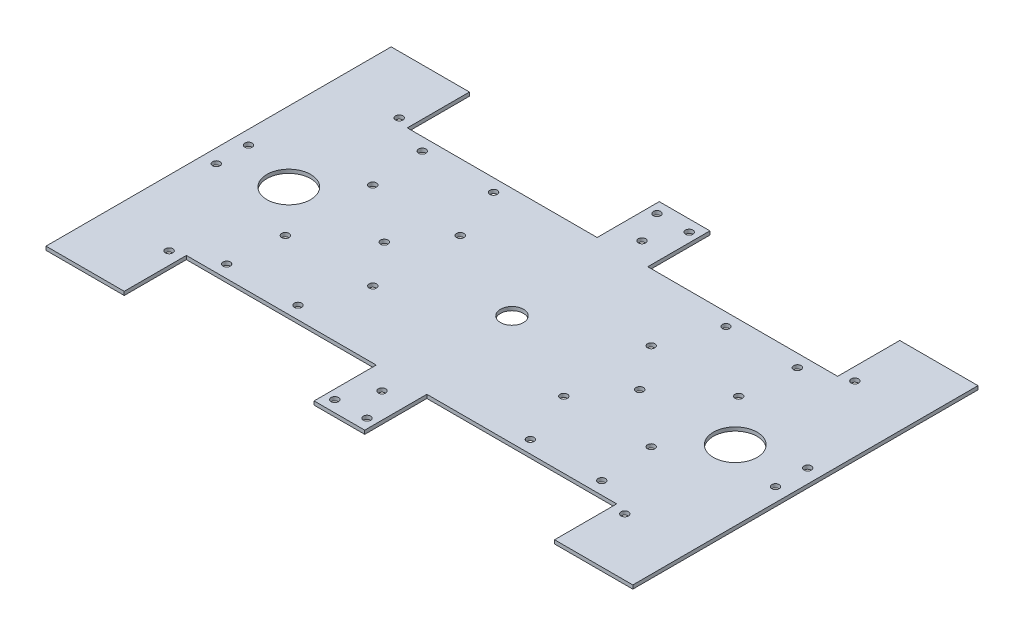
SolidWorks part; units mm, degrees
ref_plane "前视基准面" through (0, 0, 0) normal (0, 0, 1) x (1, 0, 0)
ref_plane "上视基准面" through (0, 0, 0) normal (0, 1, 0) x (1, 0, 0)
ref_plane "右视基准面" through (0, 0, 0) normal (1, 0, 0) x (0, 0, -1)
other "Configuration Table"
sketch "草图2" plane through (0, 0, 0) normal (0, 1, 0) x (1, 0, 0)
  line L0 (-11, 75) -> (11, 75)
  line L1 (-127.5, 75) -> (-93.5, 75)
  line L2 (-127.5, 75) -> (-127.5, -75)
  line L3 (-127.5, -75) -> (-93.5, -75)
  line L4 (127.5, 75) -> (127.5, -75)
  line L16 (-11, 75) -> (-11, 48)
  line L17 (-127.5, 75) -> (-93.5, 75)
  line L19 (0, 75) -> (0, -75) construction
  line L20 (-93.5, 75) -> (-93.5, 48)
  line L21 (-93.5, 48) -> (-11, 48)
  line L22 (93.5, 48) -> (11, 48)
  line L23 (11, 75) -> (11, 48)
  line L24 (93.5, 75) -> (93.5, 48)
  line L25 (-127.5, 0) -> (127.5, 0) construction
  line L26 (93.5, -75) -> (93.5, -48)
  line L27 (93.5, -48) -> (11, -48)
  line L28 (11, -75) -> (11, -48)
  line L29 (-11, -75) -> (-11, -48)
  line L30 (-93.5, -48) -> (-11, -48)
  line L31 (-93.5, -75) -> (-93.5, -48)
  line L32 (-11, 75) -> (11, 75)
  line L33 (93.5, 75) -> (127.5, 75)
  line L34 (-11, -75) -> (11, -75)
  line L35 (93.5, -75) -> (127.5, -75)
  circle A5 centre (0, 0) radius 5
  point P0 (0, 0)
  point P5 (0.2034, 0.1197)
  point P8 (-127.5, 0)
  point P9 (0.2034, 0.1197)
  point P12 (0.2034, 0.1197)
  point P14 (0, 75)
  point P17 (0.2034, 0.1197)
  point P26 (0, 0)
  dimension "D3" = 27
  dimension "D6" = 10
  dimension "D1" = 255
  dimension "D2" = 150
  dimension "D4" = 34
  dimension "D5" = 22
extrude "凸台-拉伸1" add sketch "草图2" along normal mid plane 1.6
sketch "草图3" plane through (0, 0.8, 0) normal (0, 1, 0) x (1, 0, 0)
  line L0 (-11, -48) -> (-16.5, -48)
  line L1 (0, 75) -> (0, -75) construction
  line L2 (-16.5, -48) -> (-71.5, -48)
  line L3 (-16.5, -48) -> (-16.5, -46)
  line L4 (-16.5, -46) -> (-71.5, -46)
  line L5 (-71.5, -48) -> (-71.5, -46)
  line L6 (-127.5, 0) -> (127.5, 0) construction
  line L7 (16.5, -46) -> (71.5, -46)
  line L8 (71.5, -48) -> (71.5, -46)
  line L9 (16.5, -48) -> (71.5, -48)
  line L10 (16.5, -48) -> (16.5, -46)
  line L11 (16.5, 48) -> (16.5, 46)
  line L12 (16.5, 48) -> (71.5, 48)
  line L13 (71.5, 48) -> (71.5, 46)
  line L14 (16.5, 46) -> (71.5, 46)
  line L15 (-16.5, 46) -> (-71.5, 46)
  line L16 (-71.5, 48) -> (-71.5, 46)
  line L17 (-16.5, 48) -> (-71.5, 48)
  line L18 (-16.5, 48) -> (-16.5, 46)
  line L20 (93.5, -48) -> (93.5, -75)
  line L21 (93.5, -75) -> (127.5, -75)
  line L22 (127.5, -75) -> (127.5, 75)
  line L23 (127.5, 75) -> (93.5, 75)
  line L24 (93.5, 75) -> (93.5, 48)
  line L25 (93.5, 48) -> (11, 48)
  line L26 (11, 48) -> (11, 75)
  line L27 (11, 75) -> (-11, 75)
  line L28 (-11, 75) -> (-11, 48)
  line L29 (-11, 48) -> (-93.5, 48)
  line L30 (-93.5, 48) -> (-93.5, 75)
  line L31 (-93.5, 75) -> (-127.5, 75)
  line L32 (-127.5, 75) -> (-127.5, -75)
  line L33 (-127.5, -75) -> (-93.5, -75)
  line L34 (-93.5, -75) -> (-93.5, -48)
  line L35 (-93.5, -48) -> (-11, -48)
  line L36 (-11, -48) -> (-11, -75)
  line L37 (-11, -75) -> (11, -75)
  line L38 (11, -75) -> (11, -48)
  line L39 (11, -48) -> (93.5, -48)
  line L40 (93.5, -48) -> (93.5, -75)
  line L41 (93.5, -75) -> (127.5, -75)
  line L42 (127.5, -75) -> (127.5, 75)
  line L43 (127.5, 75) -> (93.5, 75)
  line L44 (93.5, 75) -> (93.5, 48)
  line L45 (93.5, 48) -> (11, 48)
  line L46 (11, 48) -> (11, 75)
  line L47 (11, 75) -> (-11, 75)
  line L48 (-11, 75) -> (-11, 48)
  line L49 (-11, 48) -> (-93.5, 48)
  line L50 (-93.5, 48) -> (-93.5, 75)
  line L51 (-93.5, 75) -> (-127.5, 75)
  line L52 (-127.5, 75) -> (-127.5, -75)
  line L53 (-127.5, -75) -> (-93.5, -75)
  line L54 (-93.5, -75) -> (-93.5, -48)
  line L55 (-93.5, -48) -> (-11, -48)
  line L56 (-11, -48) -> (-11, -75)
  line L57 (-11, -75) -> (11, -75)
  line L58 (11, -75) -> (11, -48)
  line L59 (11, -48) -> (93.5, -48)
  point P20 (0, 0)
  dimension "D2" = 5.5
  dimension "D3" = 2
  dimension "D4" = 55
  dimension "D1" = 0
sketch "草图5" plane through (0, -0.8, 0) normal (0, -1, 0) x (1, 0, 0)
  line L0 (0, -56.5) -> (0, 56.5) construction
  line L1 (0, 0) -> (0, 70) construction
  line L2 (7, 70) -> (-7, 70) construction
  line L3 (55.5, 0) -> (-55.5, 0) construction
  line L4 (99, -50) -> (-99, -50) construction
  line L5 (99, -50) -> (99, 50) construction
  line L6 (99, 50) -> (-99, 50) construction
  line L7 (-99, -50) -> (-99, 50) construction
  line L8 (99, -50) -> (-99, 50) construction
  line L9 (99, 50) -> (-99, -50) construction
  line L10 (-85.5, 80.6) -> (-85.5, 50) construction
  line L11 (-85.5, 80.6) -> (-85.5, 50)
  line L12 (-25.5, 50) -> (-25.5, 80.6) construction
  line L13 (-25.5, 50) -> (-25.5, 80.6)
  line L14 (-85.5, 50) -> (-25.5, 50)
  line L15 (-55.5, 50) -> (-55.5, 0)
  line L16 (55.5, 50) -> (55.5, 0)
  line L17 (-55.5, 0) -> (-81.5, 0)
  line L18 (-81.5, 42.5) -> (-81.5, -42.5) construction
  line L19 (-99, 0) -> (-97, 0)
  line L20 (-81.5, 0) -> (-121.5, 0) construction
  line L21 (-121.5, 0) -> (-121.5, -7) construction
  line L22 (-81.5, 0) -> (-79.5, 0) construction
  line L23 (-79.5, 0) -> (-79.5, 19) construction
  line L24 (-79.5, 19) -> (-41.5, 19) construction
  circle A0 centre (0, 56.5) radius 1.6
  circle A1 centre (7, 70) radius 1.6
  circle A2 centre (-7, 70) radius 1.6
  circle A3 centre (99, 50) radius 1.6
  circle A4 centre (-55.5, 0) radius 1.6
  circle A5 centre (-81.5, -42.5) radius 1.6
  circle A6 centre (-50.5, -42.5) radius 1.6
  circle A7 centre (-99, -50) radius 1.6
  circle A8 centre (-97, 0) radius 9.5
  circle A9 centre (-121.5, -7) radius 1.6
  circle A10 centre (55.5, 0) radius 1.6
  circle A11 centre (81.5, -42.5) radius 1.6
  circle A12 centre (50.5, -42.5) radius 1.6
  circle A13 centre (99, -50) radius 1.6
  circle A14 centre (121.5, -7) radius 1.6
  circle A15 centre (97, 0) radius 9.5
  circle A16 centre (7, -70) radius 1.6
  circle A17 centre (-7, -70) radius 1.6
  circle A18 centre (0, -56.5) radius 1.6
  circle A19 centre (50.5, 42.5) radius 1.6
  circle A20 centre (81.5, 42.5) radius 1.6
  circle A21 centre (99, 50) radius 1.6
  circle A22 centre (121.5, 7) radius 1.6
  circle A23 centre (-50.5, 42.5) radius 1.6
  circle A24 centre (-121.5, 7) radius 1.6
  circle A25 centre (-81.5, 42.5) radius 1.6
  circle A26 centre (-99, 50) radius 1.6
  circle A27 centre (-79.5, 19) radius 1.6
  circle A28 centre (-41.5, 19) radius 1.6
  circle A29 centre (-41.5, -19) radius 1.6
  circle A30 centre (-79.5, -19) radius 1.6
  circle A31 centre (41.5, 19) radius 1.6
  circle A32 centre (79.5, 19) radius 1.6
  circle A33 centre (41.5, -19) radius 1.6
  circle A34 centre (79.5, -19) radius 1.6
  point P5 (0, 0)
  point P12 (0, 70)
  point P22 (0, 0)
  point P33 (-81.5, 0)
  dimension "D2" = 3.2
  dimension "D4" = 3.2
  dimension "D5" = 3.2
  dimension "D8" = 3.2
  dimension "D10" = 3.2
  dimension "D12" = 40
  dimension "D13" = 3.2
  dimension "D18" = 3.2
  dimension "D1" = 113
  dimension "D3" = 70
  dimension "D6" = 85
  dimension "D7" = 26
  dimension "D9" = 31
  dimension "D11" = 2
  dimension "D14" = 7
  dimension "D15" = 2
  dimension "D16" = 19
  dimension "D17" = 38
extrude "切除-拉伸1" cut sketch "草图5" against normal blind 2
sketch "草图6" plane through (0, -0.8, 0) normal (0, -1, 0) x (1, 0, 0)
  circle A0 centre (-99, -50) radius 1.6 construction
  circle A1 centre (-99, -50) radius 1.6
  circle A2 centre (0, -56.5) radius 1.6 construction
  circle A3 centre (0, -56.5) radius 1.6
  circle A4 centre (-50.5, -42.5) radius 1.6 construction
  circle A5 centre (-41.5, -19) radius 1.6 construction
  circle A6 centre (-79.5, -19) radius 1.6 construction
  circle A7 centre (-81.5, -42.5) radius 1.6 construction
  circle A8 centre (-50.5, -42.5) radius 1.6
  circle A9 centre (-41.5, -19) radius 1.6
  circle A10 centre (-79.5, -19) radius 1.6
  circle A11 centre (-81.5, -42.5) radius 1.6
  circle A12 centre (-7, -70) radius 1.6 construction
  circle A13 centre (-7, -70) radius 1.6
